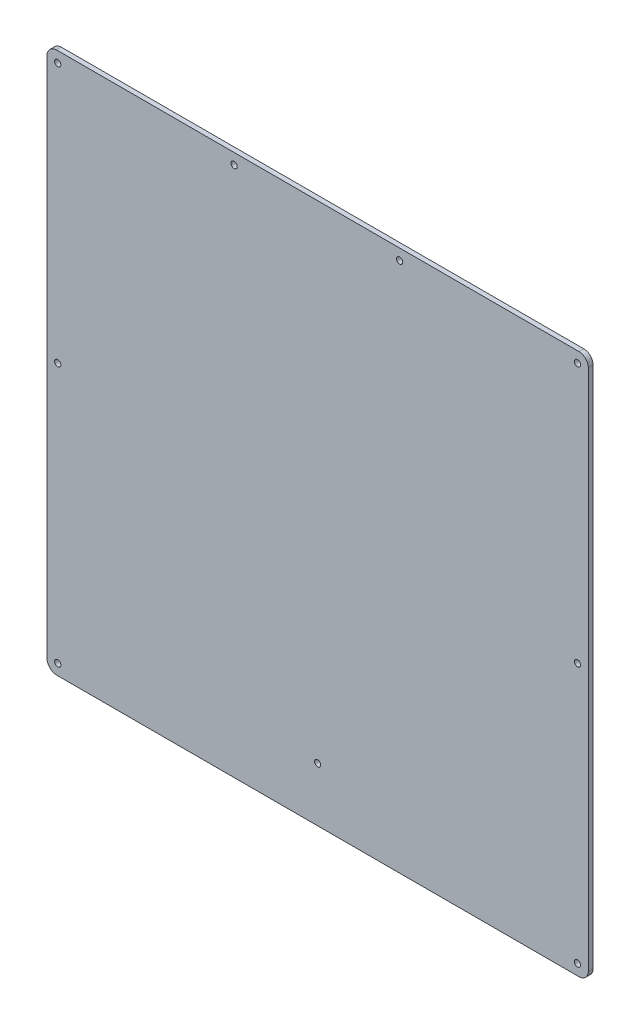
SolidWorks part; units mm, degrees
ref_plane "Front Plane" through (0, 0, 0) normal (0, 0, 1) x (1, 0, 0)
ref_plane "Top Plane" through (0, 0, 0) normal (0, 1, 0) x (1, 0, 0)
ref_plane "Right Plane" through (0, 0, 0) normal (1, 0, 0) x (0, 0, -1)
sketch "Model" plane through (0, 0, 0) normal (0, 0, 1) x (1, 0, 0)
  line L0 (3, 0) -> (172, 0)
  line L1 (172, 175) -> (3, 175)
  line L2 (0, 171.5) -> (0, 3.5)
  line L3 (175, 3) -> (175, 172)
  arc A0 (3, 175) -> (0, 171.5) centre (3.25, 171.75) ccw
  arc A1 (175, 172) -> (172, 175) centre (172, 172) ccw
  arc A2 (0, 3.5) -> (3, 0) centre (3.25, 3.25) ccw
  arc A3 (172, 0) -> (175, 3) centre (172, 3) ccw
  circle A4 centre (3.5, 3.5) radius 1
  circle A5 centre (87.5, 17.5) radius 1
  circle A6 centre (171.5, 3.5) radius 1
  circle A7 centre (171.5, 87.5) radius 1
  circle A8 centre (3.5, 87.5) radius 1
  circle A12 centre (171.5, 171.5) radius 1
  circle A13 centre (60.5, 171.5) radius 1
  circle A14 centre (3.5, 171.5) radius 1
  circle A15 centre (114, 171.5) radius 1
extrude "Boss-Extrude1" add sketch "Model" along normal blind 1.55
sketch "Sketch3" plane through (0, 0, 1.55) normal (0, 0, 1) x (1, 0, 0)
  line L0 (172, 175) -> (3, 175) construction
  line L1 (87.5, 175) -> (87.5, 0) construction
  line L2 (3, 0) -> (172, 0) construction
  line L3 (0, 87.5) -> (175, 87.5) construction
  line L4 (0, 171.5) -> (0, 3.5) construction
  line L5 (175, 3) -> (175, 172) construction
sketch "Sketch4" plane through (0, 0, 1.55) normal (0, 0, 1) x (1, 0, 0)
  line L0 (87.5, 175) -> (87.5, 0) construction
  point P0 (87.5, 87.5)
